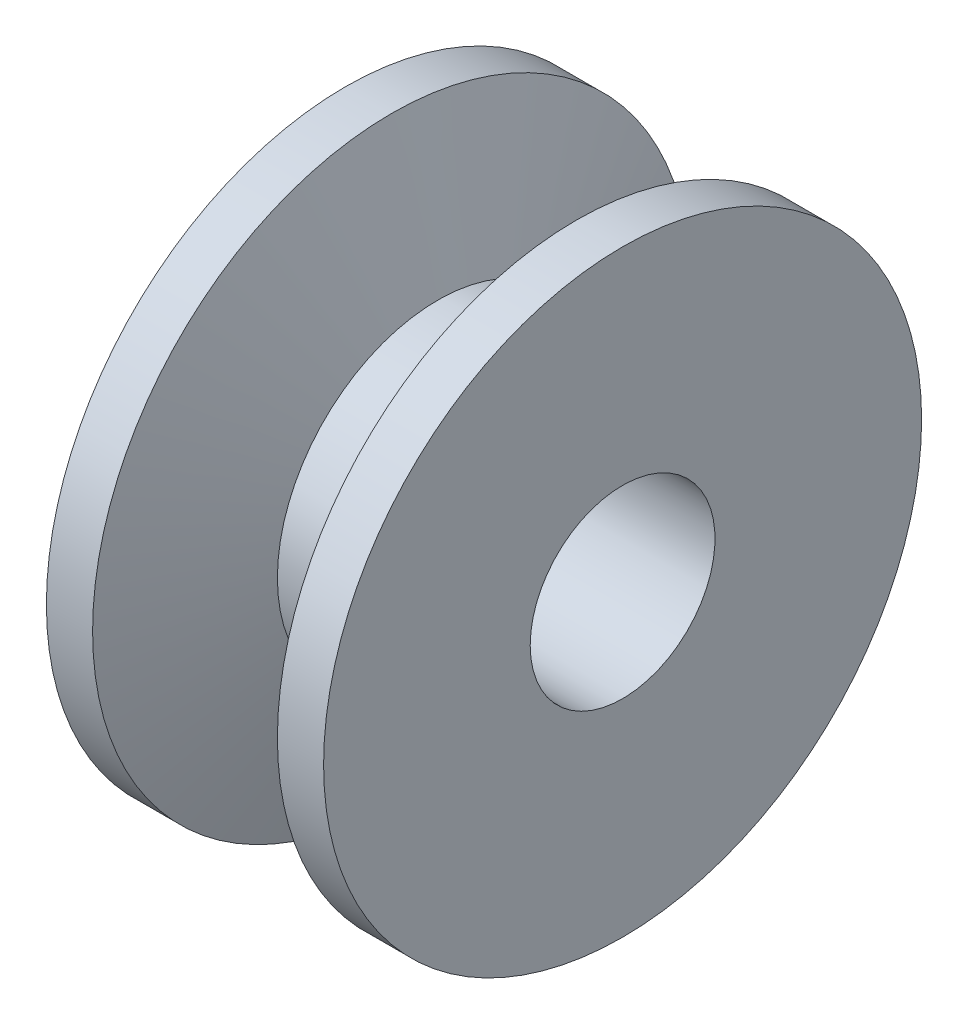
SolidWorks part; units mm, degrees
ref_plane "Plan de face" through (0, 0, 0) normal (0, 0, 1) x (1, 0, 0)
ref_plane "Plan de dessus" through (0, 0, 0) normal (0, 1, 0) x (1, 0, 0)
ref_plane "Plan de droite" through (0, 0, 0) normal (1, 0, 0) x (0, 0, -1)
sketch "Esquisse1" plane through (0, 0, 0) normal (0, 0, 1) x (1, 0, 0)
  line L0 (0, 9.9085) -> (0, -8.315) construction
  line L1 (-3, 3.7505) -> (3, 3.7505)
  line L2 (3, 3.7505) -> (3, 8.2223)
  line L3 (3, 8.2223) -> (2, 8.2223)
  line L4 (2, 8.2223) -> (1, 5.2223)
  line L5 (1, 5.2223) -> (-1, 5.2223)
  line L6 (-9.7518, 1.7505) -> (10.5095, 1.7505) construction
  line L7 (-2, 8.2223) -> (-1, 5.2223)
  line L8 (-3, 8.2223) -> (-2, 8.2223)
  line L9 (-3, 3.7505) -> (-3, 8.2223)
  point P12 (0, 5.2223)
  point P15 (0, 3.7505)
  dimension "D1" = 3
  dimension "D2" = 3
  dimension "D3" = 1
  dimension "D4" = 1
  dimension "D5" = 2
revolve "Révolution1" add sketch "Esquisse1" angle 360 about L6
